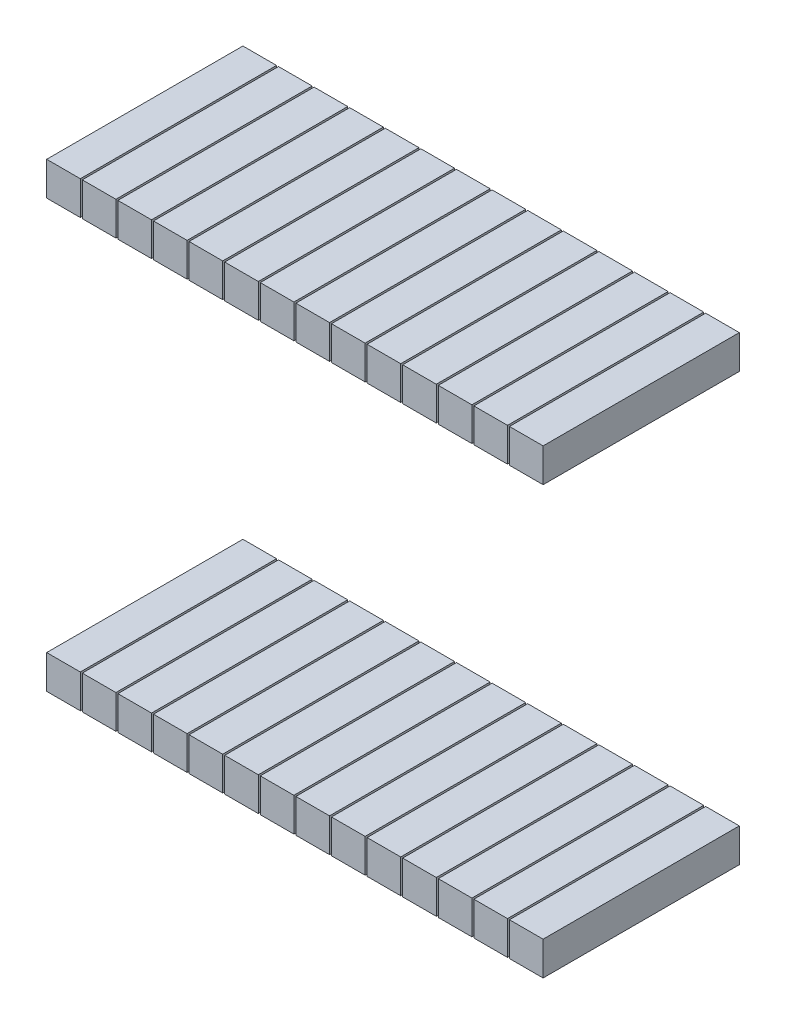
SolidWorks part; units mm, degrees
ref_plane "Front Plane" through (0, 0, 0) normal (0, 0, 1) x (1, 0, 0)
ref_plane "Top Plane" through (0, 0, 0) normal (0, 1, 0) x (1, 0, 0)
ref_plane "Right Plane" through (0, 0, 0) normal (1, 0, 0) x (0, 0, -1)
ref_plane "PZ_m9_80" through (0, 0, -9.8) normal (0, 0, 1) x (1, 0, 0)
sketch "Housings_Sk1" plane through (0, 0, -9.8) normal (0, 0, 1) x (1, 0, 0)
  line L0 (-39.5, -5.85) -> (-37.1, -5.85)
  line L1 (-37.1, -5.85) -> (-37.1, -3.45)
  line L2 (-37.1, -3.45) -> (-39.5, -3.45)
  line L3 (-39.5, -3.45) -> (-39.5, -5.85)
  line L4 (-36.96, -5.85) -> (-34.56, -5.85)
  line L5 (-34.56, -5.85) -> (-34.56, -3.45)
  line L6 (-34.56, -3.45) -> (-36.96, -3.45)
  line L7 (-36.96, -3.45) -> (-36.96, -5.85)
  line L8 (-34.42, -5.85) -> (-32.02, -5.85)
  line L9 (-32.02, -5.85) -> (-32.02, -3.45)
  line L10 (-32.02, -3.45) -> (-34.42, -3.45)
  line L11 (-34.42, -3.45) -> (-34.42, -5.85)
  line L12 (-31.88, -5.85) -> (-29.48, -5.85)
  line L13 (-29.48, -5.85) -> (-29.48, -3.45)
  line L14 (-29.48, -3.45) -> (-31.88, -3.45)
  line L15 (-31.88, -3.45) -> (-31.88, -5.85)
  line L16 (-29.34, -5.85) -> (-26.94, -5.85)
  line L17 (-26.94, -5.85) -> (-26.94, -3.45)
  line L18 (-26.94, -3.45) -> (-29.34, -3.45)
  line L19 (-29.34, -3.45) -> (-29.34, -5.85)
  line L20 (-26.8, -5.85) -> (-24.4, -5.85)
  line L21 (-24.4, -5.85) -> (-24.4, -3.45)
  line L22 (-24.4, -3.45) -> (-26.8, -3.45)
  line L23 (-26.8, -3.45) -> (-26.8, -5.85)
  line L24 (-24.26, -5.85) -> (-21.86, -5.85)
  line L25 (-21.86, -5.85) -> (-21.86, -3.45)
  line L26 (-21.86, -3.45) -> (-24.26, -3.45)
  line L27 (-24.26, -3.45) -> (-24.26, -5.85)
  line L28 (-21.72, -5.85) -> (-19.32, -5.85)
  line L29 (-19.32, -5.85) -> (-19.32, -3.45)
  line L30 (-19.32, -3.45) -> (-21.72, -3.45)
  line L31 (-21.72, -3.45) -> (-21.72, -5.85)
  line L32 (-19.18, -5.85) -> (-16.78, -5.85)
  line L33 (-16.78, -5.85) -> (-16.78, -3.45)
  line L34 (-16.78, -3.45) -> (-19.18, -3.45)
  line L35 (-19.18, -3.45) -> (-19.18, -5.85)
  line L36 (-16.64, -5.85) -> (-14.24, -5.85)
  line L37 (-14.24, -5.85) -> (-14.24, -3.45)
  line L38 (-14.24, -3.45) -> (-16.64, -3.45)
  line L39 (-16.64, -3.45) -> (-16.64, -5.85)
  line L40 (-14.1, -5.85) -> (-11.7, -5.85)
  line L41 (-11.7, -5.85) -> (-11.7, -3.45)
  line L42 (-11.7, -3.45) -> (-14.1, -3.45)
  line L43 (-14.1, -3.45) -> (-14.1, -5.85)
  line L44 (-11.56, -5.85) -> (-9.16, -5.85)
  line L45 (-9.16, -5.85) -> (-9.16, -3.45)
  line L46 (-9.16, -3.45) -> (-11.56, -3.45)
  line L47 (-11.56, -3.45) -> (-11.56, -5.85)
  line L48 (-9.02, -5.85) -> (-6.62, -5.85)
  line L49 (-6.62, -5.85) -> (-6.62, -3.45)
  line L50 (-6.62, -3.45) -> (-9.02, -3.45)
  line L51 (-9.02, -3.45) -> (-9.02, -5.85)
  line L52 (-6.48, -5.85) -> (-4.08, -5.85)
  line L53 (-4.08, -5.85) -> (-4.08, -3.45)
  line L54 (-4.08, -3.45) -> (-6.48, -3.45)
  line L55 (-6.48, -3.45) -> (-6.48, -5.85)
  line L56 (-39.5, 24.63) -> (-37.1, 24.63)
  line L57 (-37.1, 24.63) -> (-37.1, 27.03)
  line L58 (-37.1, 27.03) -> (-39.5, 27.03)
  line L59 (-39.5, 27.03) -> (-39.5, 24.63)
  line L60 (-36.96, 24.63) -> (-34.56, 24.63)
  line L61 (-34.56, 24.63) -> (-34.56, 27.03)
  line L62 (-34.56, 27.03) -> (-36.96, 27.03)
  line L63 (-36.96, 27.03) -> (-36.96, 24.63)
  line L64 (-34.42, 24.63) -> (-32.02, 24.63)
  line L65 (-32.02, 24.63) -> (-32.02, 27.03)
  line L66 (-32.02, 27.03) -> (-34.42, 27.03)
  line L67 (-34.42, 27.03) -> (-34.42, 24.63)
  line L68 (-31.88, 24.63) -> (-29.48, 24.63)
  line L69 (-29.48, 24.63) -> (-29.48, 27.03)
  line L70 (-29.48, 27.03) -> (-31.88, 27.03)
  line L71 (-31.88, 27.03) -> (-31.88, 24.63)
  line L72 (-29.34, 24.63) -> (-26.94, 24.63)
  line L73 (-26.94, 24.63) -> (-26.94, 27.03)
  line L74 (-26.94, 27.03) -> (-29.34, 27.03)
  line L75 (-29.34, 27.03) -> (-29.34, 24.63)
  line L76 (-26.8, 24.63) -> (-24.4, 24.63)
  line L77 (-24.4, 24.63) -> (-24.4, 27.03)
  line L78 (-24.4, 27.03) -> (-26.8, 27.03)
  line L79 (-26.8, 27.03) -> (-26.8, 24.63)
  line L80 (-24.26, 24.63) -> (-21.86, 24.63)
  line L81 (-21.86, 24.63) -> (-21.86, 27.03)
  line L82 (-21.86, 27.03) -> (-24.26, 27.03)
  line L83 (-24.26, 27.03) -> (-24.26, 24.63)
  line L84 (-21.72, 24.63) -> (-19.32, 24.63)
  line L85 (-19.32, 24.63) -> (-19.32, 27.03)
  line L86 (-19.32, 27.03) -> (-21.72, 27.03)
  line L87 (-21.72, 27.03) -> (-21.72, 24.63)
  line L88 (-19.18, 24.63) -> (-16.78, 24.63)
  line L89 (-16.78, 24.63) -> (-16.78, 27.03)
  line L90 (-16.78, 27.03) -> (-19.18, 27.03)
  line L91 (-19.18, 27.03) -> (-19.18, 24.63)
  line L92 (-16.64, 24.63) -> (-14.24, 24.63)
  line L93 (-14.24, 24.63) -> (-14.24, 27.03)
  line L94 (-14.24, 27.03) -> (-16.64, 27.03)
  line L95 (-16.64, 27.03) -> (-16.64, 24.63)
  line L96 (-14.1, 24.63) -> (-11.7, 24.63)
  line L97 (-11.7, 24.63) -> (-11.7, 27.03)
  line L98 (-11.7, 27.03) -> (-14.1, 27.03)
  line L99 (-14.1, 27.03) -> (-14.1, 24.63)
  line L100 (-11.56, 24.63) -> (-9.16, 24.63)
  line L101 (-9.16, 24.63) -> (-9.16, 27.03)
  line L102 (-9.16, 27.03) -> (-11.56, 27.03)
  line L103 (-11.56, 27.03) -> (-11.56, 24.63)
  line L104 (-9.02, 24.63) -> (-6.62, 24.63)
  line L105 (-6.62, 24.63) -> (-6.62, 27.03)
  line L106 (-6.62, 27.03) -> (-9.02, 27.03)
  line L107 (-9.02, 27.03) -> (-9.02, 24.63)
  line L108 (-6.48, 24.63) -> (-4.08, 24.63)
  line L109 (-4.08, 24.63) -> (-4.08, 27.03)
  line L110 (-4.08, 27.03) -> (-6.48, 27.03)
  line L111 (-6.48, 27.03) -> (-6.48, 24.63)
extrude "Housings" add sketch "Housings_Sk1" against normal blind 14
